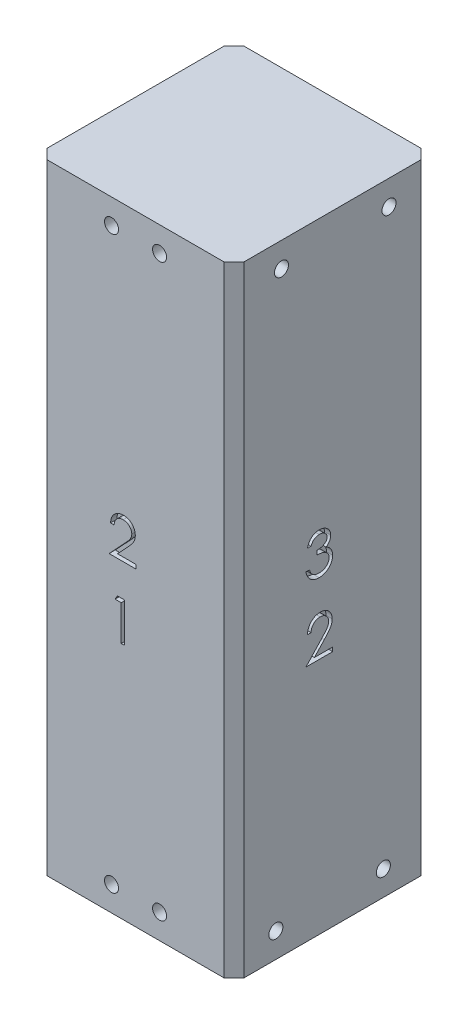
SolidWorks part; units mm, degrees
ref_plane "Front" through (0, 0, 0) normal (0, 0, 1) x (1, 0, 0)
ref_plane "Top" through (0, 0, 0) normal (0, 1, 0) x (1, 0, 0)
ref_plane "Right" through (0, 0, 0) normal (1, 0, 0) x (0, 0, -1)
sketch "Sketch1" plane through (0, 0, 0) normal (0, 1, 0) x (1, 0, 0)
  line L1 (-15.875, 15.875) -> (15.875, 15.875)
  line L2 (-15.875, 15.875) -> (-15.875, -15.875)
  line L3 (-15.875, -15.875) -> (15.875, -15.875)
  line L4 (15.875, 15.875) -> (15.875, -15.875)
  line L5 (-15.875, 15.875) -> (15.875, -15.875) construction
  line L6 (-15.875, -15.875) -> (15.875, 15.875) construction
  point P0 (0, 0)
  dimension "D1" = 31.75
  dimension "D2" = 31.75
extrude "Boss-Extrude1" add sketch "Sketch1" along normal blind 100
chamfer "Chamfer1" distance 1.5875 angle 45 4 edges at (-15.875, 50, -15.875) (15.875, 50, -15.875) (-15.875, 50, 15.875) (15.875, 50, 15.875)
sketch "Sketch2" plane through (-15.875, 0, 0) normal (-1, 0, 0) x (0, 0, 1)
  line L0 (-14.2875, 50) -> (14.2875, 50) construction
  line L1 (-14.2875, 100) -> (-14.2875, 0) construction
  line L2 (14.2875, 0) -> (14.2875, 100) construction
  text T0 "    1\r\n    4"
  point P6 (0, 50)
extrude "Cut-Extrude1" cut sketch "Sketch2" against normal blind 1
sketch "Sketch3" plane through (0, 0, 15.875) normal (0, 0, 1) x (1, 0, 0)
  line L0 (-14.2875, 50) -> (14.2875, 50) construction
  line L1 (-14.2875, 100) -> (-14.2875, 0) construction
  line L2 (14.2875, 0) -> (14.2875, 100) construction
  text T0 "    2\r\n    1"
extrude "Cut-Extrude2" cut sketch "Sketch3" against normal blind 1
sketch "Sketch4" plane through (15.875, 0, 0) normal (1, 0, 0) x (0, 0, -1)
  line L0 (-14.2875, 50) -> (14.2875, 50) construction
  line L1 (-14.2875, 100) -> (-14.2875, 0) construction
  line L2 (14.2875, 0) -> (14.2875, 100) construction
  text T0 "    3\r\n    2"
extrude "Cut-Extrude3" cut sketch "Sketch4" against normal blind 1
sketch "Sketch5" plane through (0, 0, -15.875) normal (0, 0, -1) x (-1, 0, 0)
  line L0 (-14.2875, 50) -> (14.2875, 50) construction
  line L1 (-14.2875, 100) -> (-14.2875, 0) construction
  line L2 (14.2875, 0) -> (14.2875, 100) construction
  text T0 "    4\r\n    3"
extrude "Cut-Extrude4" cut sketch "Sketch5" against normal blind 1
extrude "Cut-Extrude5" cut sketch "Sketch6" against normal blind 7
sketch "Sketch6" plane through (-15.875, 23.8161, -46.1775) normal (-1, 0, 0) x (0, 0, 1)
  circle A0 centre (50.0525, 72.1839) radius 1.1303
  circle A1 centre (52.8087, 56.0639) radius 0.889
  circle A2 centre (57.6087, 56.0639) radius 0.889
  circle A3 centre (50.0525, -19.8161) radius 1.1303
  circle A4 centre (42.3025, 72.1839) radius 1.1303
  circle A5 centre (42.3025, -19.8161) radius 1.1303
extrude "Cut-Extrude6" cut sketch "Sketch7" against normal blind 7
sketch "Sketch7" plane through (121.2205, 23.8161, 15.875) normal (0, 0, 1) x (1, 0, 0)
  circle A0 centre (-125.0955, 72.1839) radius 1.1303
  circle A1 centre (-117.3455, 72.1839) radius 1.1303
  circle A2 centre (-125.0955, -19.8161) radius 1.1303
  circle A3 centre (-117.3455, -19.8161) radius 1.1303
extrude "Cut-Extrude7" cut sketch "Sketch8" against normal blind 7
sketch "Sketch8" plane through (15.875, 23.8161, -46.1775) normal (1, 0, 0) x (0, 0, -1)
  circle A0 centre (-54.39, 72.1839) radius 1.1303
  circle A1 centre (-37.055, 72.1839) radius 1.1303
  circle A2 centre (-55.3, -19.8161) radius 1.1303
  circle A3 centre (-37.965, -19.8161) radius 1.1303
extrude "Cut-Extrude8" cut sketch "Sketch9" against normal blind 7
sketch "Sketch9" plane through (121.2205, 23.8161, -15.875) normal (0, 0, -1) x (-1, 0, 0)
  circle A0 centre (117.3455, 72.1839) radius 1.1303
  circle A1 centre (125.0955, 72.1839) radius 1.1303
  circle A2 centre (114.5892, -3.6961) radius 0.889
  circle A3 centre (109.7892, -3.6961) radius 0.889
  circle A4 centre (117.3455, -19.8161) radius 1.1303
  circle A5 centre (125.0955, -19.8161) radius 1.1303
